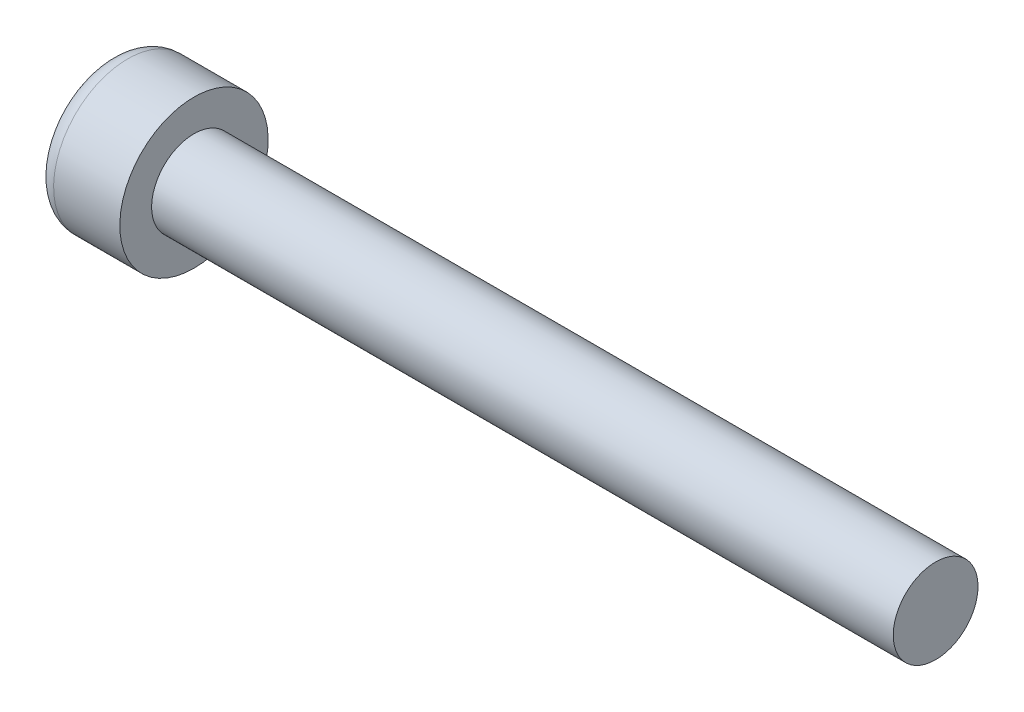
SolidWorks part; units mm, degrees
material "Plain Carbon Steel"
ref_plane "Front Plane" through (0, 0, 0) normal (0, 0, 1) x (1, 0, 0)
ref_plane "Top Plane" through (0, 0, 0) normal (0, 1, 0) x (1, 0, 0)
ref_plane "Right Plane" through (0, 0, 0) normal (1, 0, 0) x (0, 0, -1)
sketch "Sketch1" plane through (0, 0, 0) normal (0, 0, 1) x (1, 0, 0)
  line L0 (0, 0) -> (0, 2.625)
  line L1 (0.875, 3.5) -> (4, 3.5)
  line L2 (4, 3.5) -> (4, 2)
  line L3 (4, 2) -> (39, 2)
  line L4 (39, 2) -> (39, 0)
  line L5 (39, 0) -> (0, 0) construction
  line L6 (0.875, 2.625) -> (0.875, 1.75) construction
  line L7 (0.875, 1.75) -> (0.875, 0.875) construction
  line L8 (0.875, 0.875) -> (0.875, 0) construction
  line L9 (0.875, 3.5) -> (0.875, 2.625) construction
  line L10 (0, 0) -> (39, 0)
  arc A0 (0, 2.625) -> (0.875, 3.5) centre (0.875, 2.625) cw
  dimension "D1" = 4
  dimension "D2" = 7
  dimension "D3" = 4
  dimension "D4" = 35
revolve "Revolve1" add sketch "Sketch1" angle 360 about L10
sketch "Sketch2" plane through (0, 0, 0) normal (-1, 0, 0) x (0, 0, 1)
  line L1 (0, 1.7321) -> (-1.5, 0.866)
  line L2 (-1.5, 0.866) -> (-1.5, -0.866)
  line L3 (-1.5, -0.866) -> (0, -1.7321)
  line L4 (0, -1.7321) -> (1.5, -0.866)
  line L5 (1.5, -0.866) -> (1.5, 0.866)
  line L6 (1.5, 0.866) -> (0, 1.7321)
  circle A0 centre (0, 0) radius 1.5 construction
  dimension "D1" = 3
extrude "Cut-Extrude1" cut sketch "Sketch2" against normal blind 2
